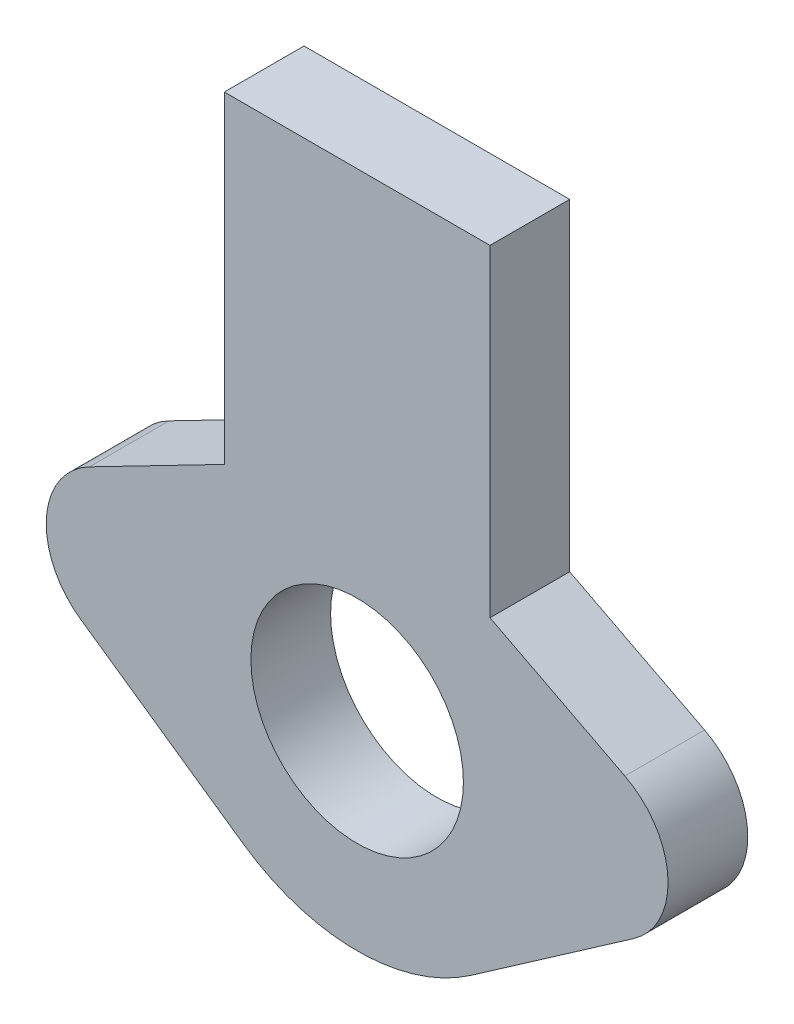
SolidWorks part; units mm, degrees
ref_plane "Front Plane" through (0, 0, 0) normal (0, 0, 1) x (1, 0, 0)
ref_plane "Top Plane" through (0, 0, 0) normal (0, 1, 0) x (1, 0, 0)
ref_plane "Right Plane" through (0, 0, 0) normal (1, 0, 0) x (0, 0, -1)
sketch "Sketch1" plane through (0, 0, 0) normal (0, 0, 1) x (1, 0, 0)
  line L0 (-5, 5.5902) -> (-5, 18)
  line L1 (-5, 18) -> (5, 18)
  line L2 (0, -55) -> (0, 55) construction
  line L3 (5, 5.5902) -> (5, 18)
  circle A0 centre (0, 0) radius 4
  arc A1 (-5, 5.5902) -> (5, 5.5902) centre (0, 0) ccw
  point P10 (0, 18)
  dimension "D1" = 8
  dimension "D2" = 15
  dimension "D3" = 18
  dimension "D4" = 5
extrude "Boss-Extrude1" add sketch "Sketch1" along normal blind 3
sketch "Sketch2" plane through (0, 0, 0) normal (0, 0, -1) x (-1, 0, 0)
  line L0 (-4.2837, -6.1563) -> (-14.5067, 0.957)
  line L1 (-14.5067, 0.957) -> (-3.4378, 6.6657)
  line L4 (0, 0) -> (0, 5.778) construction
  line L5 (4.2837, -6.1563) -> (14.5067, 0.957)
  line L6 (14.5067, 0.957) -> (3.4378, 6.6657)
  arc A1 (-5, 5.5902) -> (5, 5.5902) centre (0, 0) ccw construction
  arc A2 (-3.4378, 6.6657) -> (-4.2837, -6.1563) centre (0, 0) ccw
  arc A4 (3.4378, 6.6657) -> (4.2837, -6.1563) centre (0, 0) cw
extrude "Boss-Extrude2" add sketch "Sketch2" against normal up to surface (3 mm away) up to face at (0, 8.5225, 3)
fillet "Fillet1" radius 3 2 edges at (-14.5067, 0.957, 1.5) (14.5067, 0.957, 1.5)
sketch "Sketch3" plane through (0, 0, 0) normal (0, 0, -1) x (-1, 0, 0)
  line L1 (-2.5, 4.5) -> (2.5, 4.5)
  line L2 (-2.5, 4.5) -> (-2.5, 9.8)
  line L3 (-2.5, 9.8) -> (2.5, 9.8)
  line L4 (2.5, 4.5) -> (2.5, 9.8)
  dimension "D1" = 5
  dimension "D2" = 5.3
  dimension "D3" = 2.5
  dimension "D4" = 4.5
extrude "Cut-Extrude1" [suppressed] cut sketch "Sketch3" against normal through all
